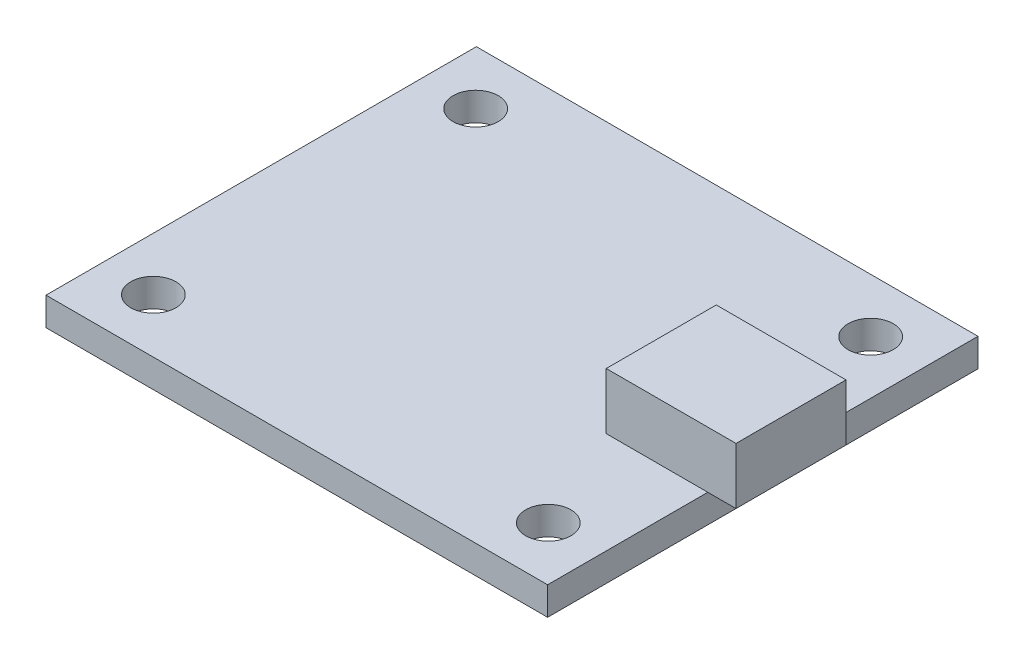
SolidWorks part; units mm, degrees
ref_plane "Front Plane" through (0, 0, 0) normal (0, 0, 1) x (1, 0, 0)
ref_plane "Top Plane" through (0, 0, 0) normal (0, 1, 0) x (1, 0, 0)
ref_plane "Right Plane" through (0, 0, 0) normal (1, 0, 0) x (0, 0, -1)
sketch "Sketch1" plane through (0, 0, 0) normal (0, 1, 0) x (1, 0, 0)
  line L1 (-17.78, 15.255) -> (17.78, 15.255)
  line L2 (-17.78, 15.255) -> (-17.78, -15.255)
  line L3 (-17.78, -15.255) -> (17.78, -15.255)
  line L4 (17.78, 15.255) -> (17.78, -15.255)
  line L5 (-17.78, 15.255) -> (17.78, -15.255) construction
  line L6 (-17.78, -15.255) -> (17.78, 15.255) construction
  point P0 (0, 0)
  dimension "D1" = 30.51
  dimension "D2" = 35.56
extrude "Boss-Extrude1" add sketch "Sketch1" along normal blind 2
sketch "Sketch2" plane through (0, 2, 0) normal (0, 1, 0) x (1, 0, 0)
  line L1 (14, 11.425) -> (-14, 11.425) construction
  line L2 (14, 11.425) -> (14, -11.425) construction
  line L3 (14, -11.425) -> (-14, -11.425) construction
  line L4 (-14, 11.425) -> (-14, -11.425) construction
  line L5 (14, 11.425) -> (-14, -11.425) construction
  line L6 (14, -11.425) -> (-14, 11.425) construction
  circle A0 centre (-14, 11.425) radius 1.6
  circle A1 centre (14, 11.425) radius 1.6
  circle A2 centre (14, -11.425) radius 1.6
  circle A3 centre (-14, -11.425) radius 1.6
  point P0 (0, 0)
  dimension "D3" = 3.2
  dimension "D1" = 22.85
  dimension "D2" = 28
extrude "Cut-Extrude1" cut sketch "Sketch2" against normal through all
sketch "Sketch3" plane through (0, 2, 0) normal (0, 1, 0) x (1, 0, 0)
  line L4 (0, 0) -> (15.18, 0) construction
  line L5 (10.58, 3.9) -> (19.78, 3.9)
  line L6 (10.58, 3.9) -> (10.58, -3.9)
  line L7 (10.58, -3.9) -> (19.78, -3.9)
  line L8 (19.78, 3.9) -> (19.78, -3.9)
  line L9 (10.58, 3.9) -> (19.78, -3.9) construction
  line L10 (10.58, -3.9) -> (19.78, 3.9) construction
  line L11 (17.78, -15.255) -> (17.78, 15.255) construction
  point P2 (15.18, 0)
  dimension "D1" = 9.2
  dimension "D2" = 7.8
  dimension "D3" = 2
extrude "Boss-Extrude2" add sketch "Sketch3" along normal blind 4
